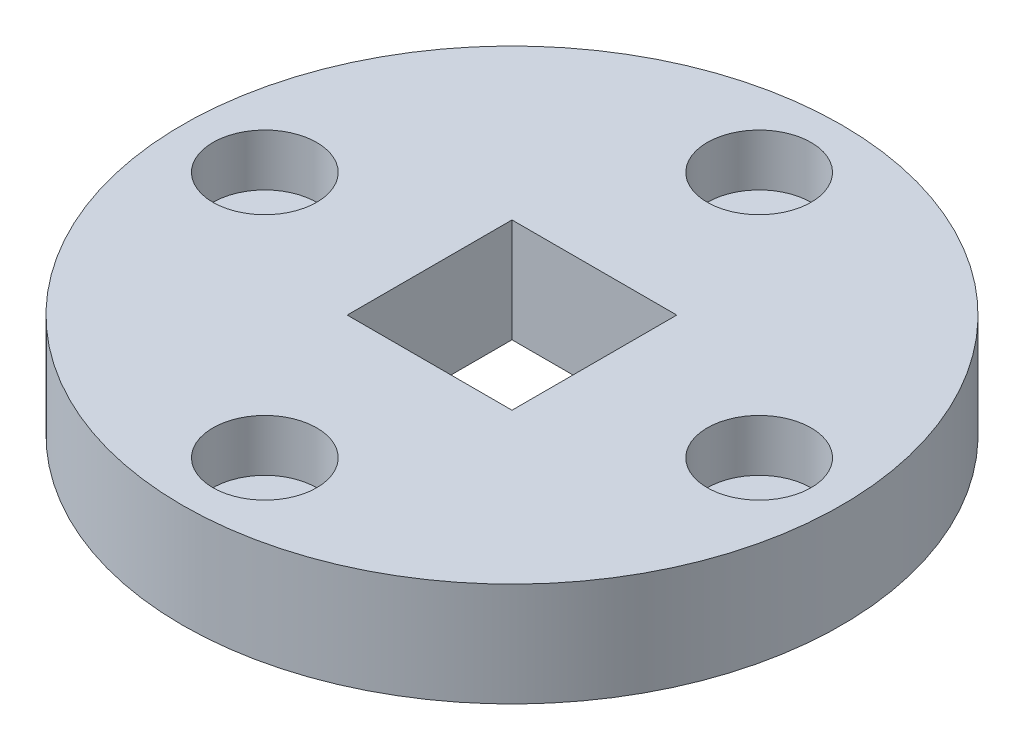
SolidWorks part; units mm, degrees
ref_plane "Front Plane" through (0, 0, 0) normal (0, 0, 1) x (1, 0, 0)
ref_plane "Top Plane" through (0, 0, 0) normal (0, 1, 0) x (1, 0, 0)
ref_plane "Right Plane" through (0, 0, 0) normal (1, 0, 0) x (0, 0, -1)
sketch "Sketch2" plane through (0, 0, 0) normal (0, 1, 0) x (1, 0, 0)
  line L1 (-1.5875, -1.5875) -> (1.5875, -1.5875)
  line L2 (-1.5875, -1.5875) -> (-1.5875, 1.5875)
  line L3 (-1.5875, 1.5875) -> (1.5875, 1.5875)
  line L4 (1.5875, -1.5875) -> (1.5875, 1.5875)
  line L5 (-1.5875, -1.5875) -> (1.5875, 1.5875) construction
  line L6 (-1.5875, 1.5875) -> (1.5875, -1.5875) construction
  circle A0 centre (0, 0) radius 6.35
  dimension "D2" = 12.7
  dimension "D1" = 3.175
extrude "Boss-Extrude1" add sketch "Sketch2" along normal blind 2
sketch "Sketch3" plane through (0, 2, 0) normal (0, 1, 0) x (1, 0, 0)
  circle A0 centre (-4.7625, 0) radius 1
  point P2 (-5.7625, 0)
  dimension "D1" = 2
  dimension "D2" = 4.7625
extrude "Cut-Extrude1" cut sketch "Sketch3" against normal blind 1
pattern_circular "CirPattern1" count 4 over 360 about axis through (0, 0, 0) along (0, 1, 0) of "Cut-Extrude1"
